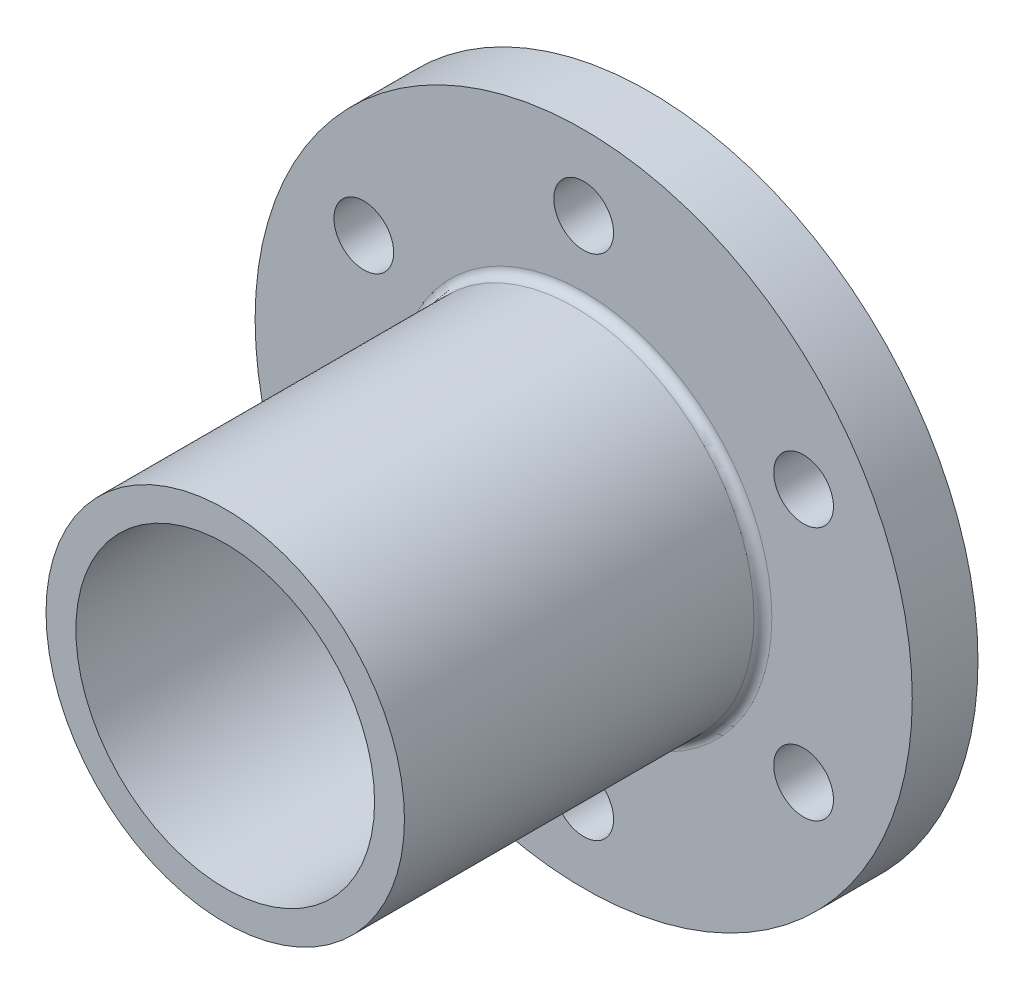
SolidWorks part; units mm, degrees
ref_plane "Front Plane" through (0, 0, 0) normal (0, 0, 1) x (1, 0, 0)
ref_plane "Top Plane" through (0, 0, 0) normal (0, 1, 0) x (1, 0, 0)
ref_plane "Right Plane" through (0, 0, 0) normal (1, 0, 0) x (0, 0, -1)
sketch "Sketch1" plane through (0, 0, 0) normal (0, 0, 1) x (1, 0, 0)
  circle A0 centre (0, 0) radius 110
  dimension "D1" = 220
extrude "Boss-Extrude1" add sketch "Sketch1" along normal blind 22
sketch "Sketch2" plane through (0, 0, 22) normal (0, 0, 1) x (1, 0, 0)
  circle A0 centre (0, 0) radius 60
  dimension "D1" = 120
extrude "Boss-Extrude2" add sketch "Sketch2" along normal blind 120
sketch "Sketch3" plane through (0, 0, 142) normal (0, 0, 1) x (1, 0, 0)
  circle A0 centre (0, 0) radius 50
  dimension "D1" = 100
extrude "Cut-Extrude1" cut sketch "Sketch3" against normal through all
sketch "Sketch4" plane through (0, 0, 22) normal (0, 0, 1) x (1, 0, 0)
  circle A0 centre (0, 85) radius 10
  circle A1 centre (73.6122, 42.5) radius 10
  circle A2 centre (73.6122, -42.5) radius 10
  circle A3 centre (0, -85) radius 10
  circle A4 centre (-73.6122, -42.5) radius 10
  circle A5 centre (-73.6122, 42.5) radius 10
  circle A6 centre (0, 0) radius 85 construction
  point P4 (0, 0)
  point P5 (0, 0)
  point P15 (0, 0)
  dimension "D1" = 20
  dimension "D2" = 85
  dimension "D3" = 6
extrude "Cut-Extrude2" cut sketch "Sketch4" against normal through all
fillet "Fillet1" radius 3 1 edges at (60, 0, 22)
